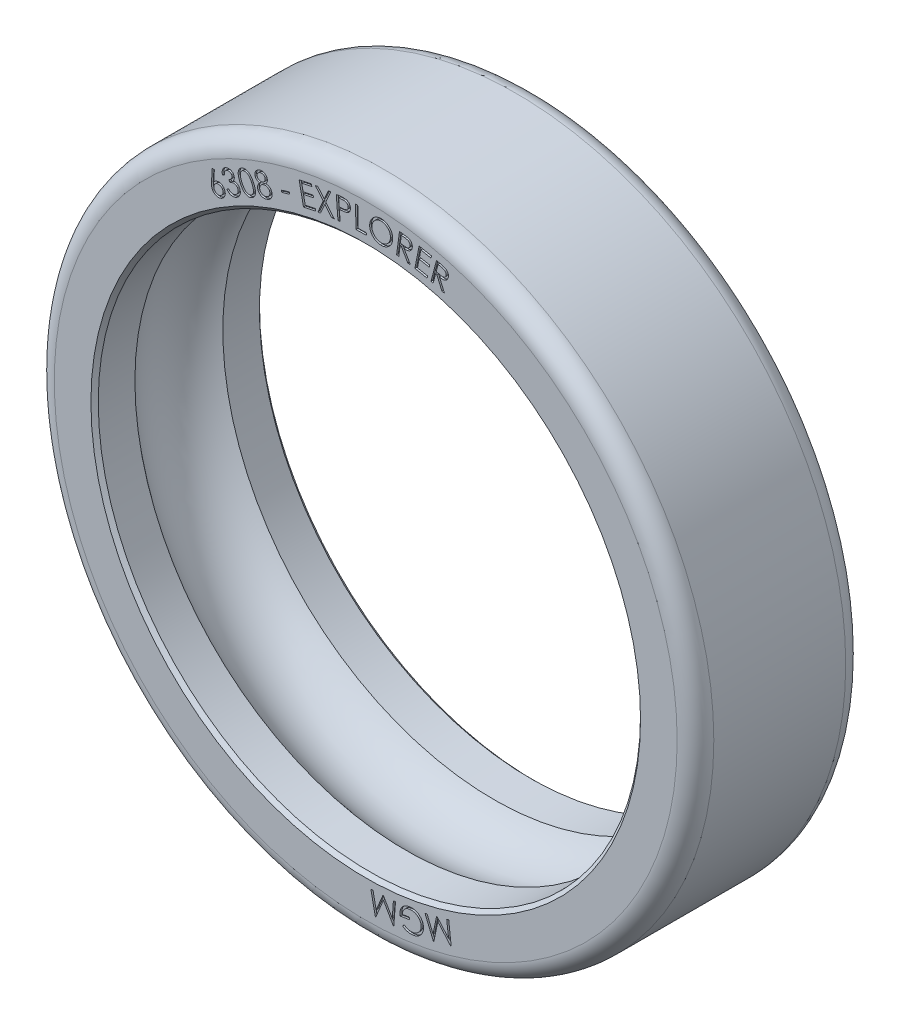
SolidWorks part; units mm, degrees
ref_plane "Front Plane" through (0, 0, 0) normal (0, 0, 1) x (1, 0, 0)
ref_plane "Top Plane" through (0, 0, 0) normal (0, 1, 0) x (1, 0, 0)
ref_plane "Right Plane" through (0, 0, 0) normal (1, 0, 0) x (0, 0, -1)
sketch "Sketch1" plane through (0, 0, 0) normal (0, 0, 1) x (1, 0, 0)
  circle A0 centre (0, 0) radius 45
  circle A1 centre (0, 0) radius 37
  dimension "D1" = 90
  dimension "D2" = 74
extrude "Boss-Extrude1" add sketch "Sketch1" along normal mid plane 23
fillet "Fillet1" radius 2.5 2 edges at (45, 0, -11.5) (45, 0, 11.5)
sketch "Sketch2" plane through (0, 0, 0) normal (0, 1, 0) x (1, 0, 0)
  line L0 (0, 0) -> (32.5, 0) construction
  line L1 (0, 0) -> (0, 25.1268) construction
  circle A0 centre (32.5, 0) radius 7.5
  dimension "D2" = 15
  dimension "D1" = 32.5
revolve "Cut-Revolve1" cut sketch "Sketch2" angle 360 about L1
chamfer "Chamfer1" distance 0.5 angle 45 2 edges at (37, 0, -11.5) (37, 0, 11.5)
sketch "Sketch3" plane through (0, 0, 11.5) normal (0, 0, 1) x (1, 0, 0)
  arc A0 (-20.6928, 32.4663) -> (-37.7662, 7.4808) centre (0, 0) cw construction
  text T0 "6308 - EXPLORER                                                                                     MGM " font "Century Gothic" height 3
  point P4 (0, 0)
  dimension "D1" = 38.5
extrude "Cut-Extrude1" cut sketch "Sketch3" against normal blind 0.25
